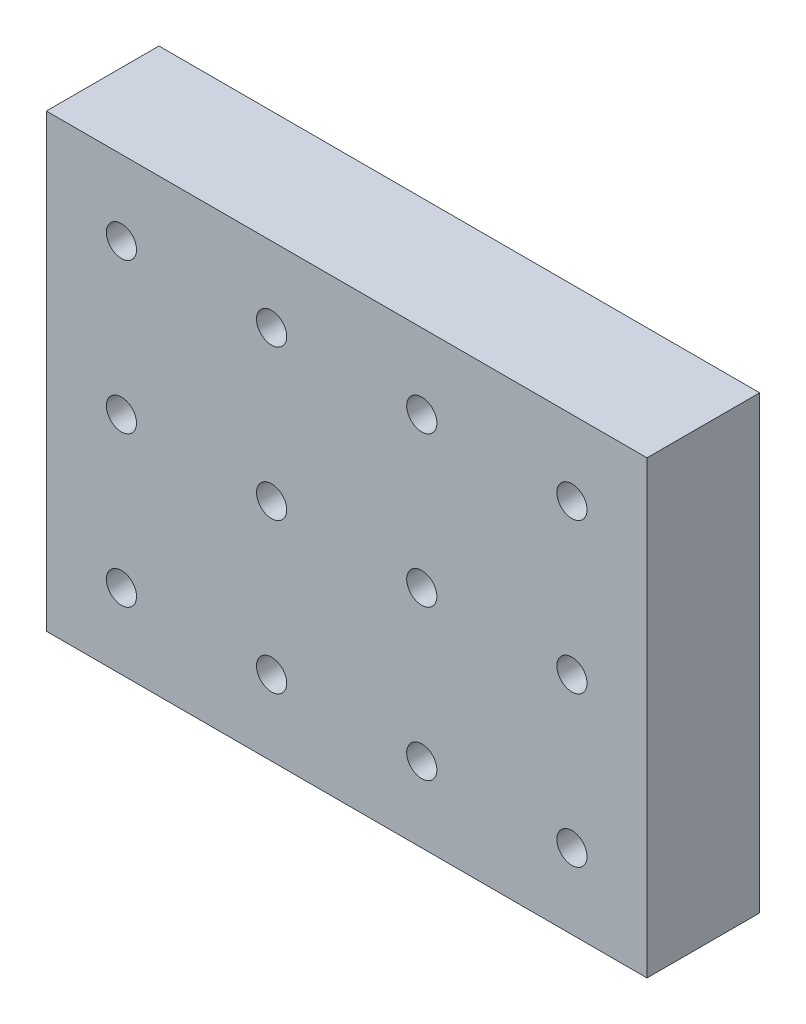
SolidWorks part; units mm, degrees
ref_plane "Front Plane" through (0, 0, 0) normal (0, 0, 1) x (1, 0, 0)
ref_plane "Top Plane" through (0, 0, 0) normal (0, 1, 0) x (1, 0, 0)
ref_plane "Right Plane" through (0, 0, 0) normal (1, 0, 0) x (0, 0, -1)
sketch "Sketch1" plane through (0, 0, 0) normal (0, 0, 1) x (1, 0, 0)
  line L1 (0, 0) -> (101.6, 0)
  line L2 (0, 0) -> (0, 76.2)
  line L3 (0, 76.2) -> (101.6, 76.2)
  line L4 (101.6, 0) -> (101.6, 76.2)
  dimension "D1" = 76.2
  dimension "D2" = 101.6
extrude "Boss-Extrude1" add sketch "Sketch1" along normal blind 19.05
hole_wizard "1/4-20 Tapped Hole1" positions "Sketch2" profile "Sketch3" tap size "1/4-20" standard "ANSI Inch" end condition through all
sketch "Sketch2" plane through (0, 0, 19.05) normal (0, 0, 1) x (1, 0, 0)
  line L0 (101.6, 76.2) -> (0, 76.2) construction
  line L1 (0, 76.2) -> (0, 0) construction
  point P0 (12.7, 63.5)
  dimension "D1" = 12.7
  dimension "D2" = 12.7
sketch "Sketch3" plane through (12.7, 63.5, 19.05) normal (1, 0, 0) x (0, -1, 0)
  line L0 (0, 0) -> (0, 19.05)
  line L1 (0, 19.05) -> (2.5527, 19.05)
  line L2 (2.5527, 19.05) -> (2.5527, 0)
  line L5 (2.5527, 0) -> (0, 0)
  line L11 (0, -6.35) -> (0, 107.95) construction
  dimension "Thru Tap Drill Dia." = 5.1054
  dimension "Thru Tap Drill Depth" = 19.05
cosmetic thread "Hole Thread1" parameters "D2"=6.35
pattern_linear "LPattern1" count 4 spacing 25.4 along (1, 0, 0) count 3 spacing 25.4 along (0, -1, 0) of "1/4-20 Tapped Hole1"
cosmetic thread "Hole Thread2" parameters "D2"=6.35
cosmetic thread "Hole Thread3" parameters "D2"=6.35
cosmetic thread "Hole Thread4" parameters "D2"=6.35
cosmetic thread "Hole Thread5" parameters "D2"=6.35
cosmetic thread "Hole Thread6" parameters "D2"=6.35
cosmetic thread "Hole Thread7" parameters "D2"=6.35
cosmetic thread "Hole Thread8" parameters "D2"=6.35
cosmetic thread "Hole Thread9" parameters "D2"=6.35
cosmetic thread "Hole Thread10" parameters "D2"=6.35
cosmetic thread "Hole Thread11" parameters "D2"=6.35
cosmetic thread "Hole Thread12" parameters "D2"=6.35
